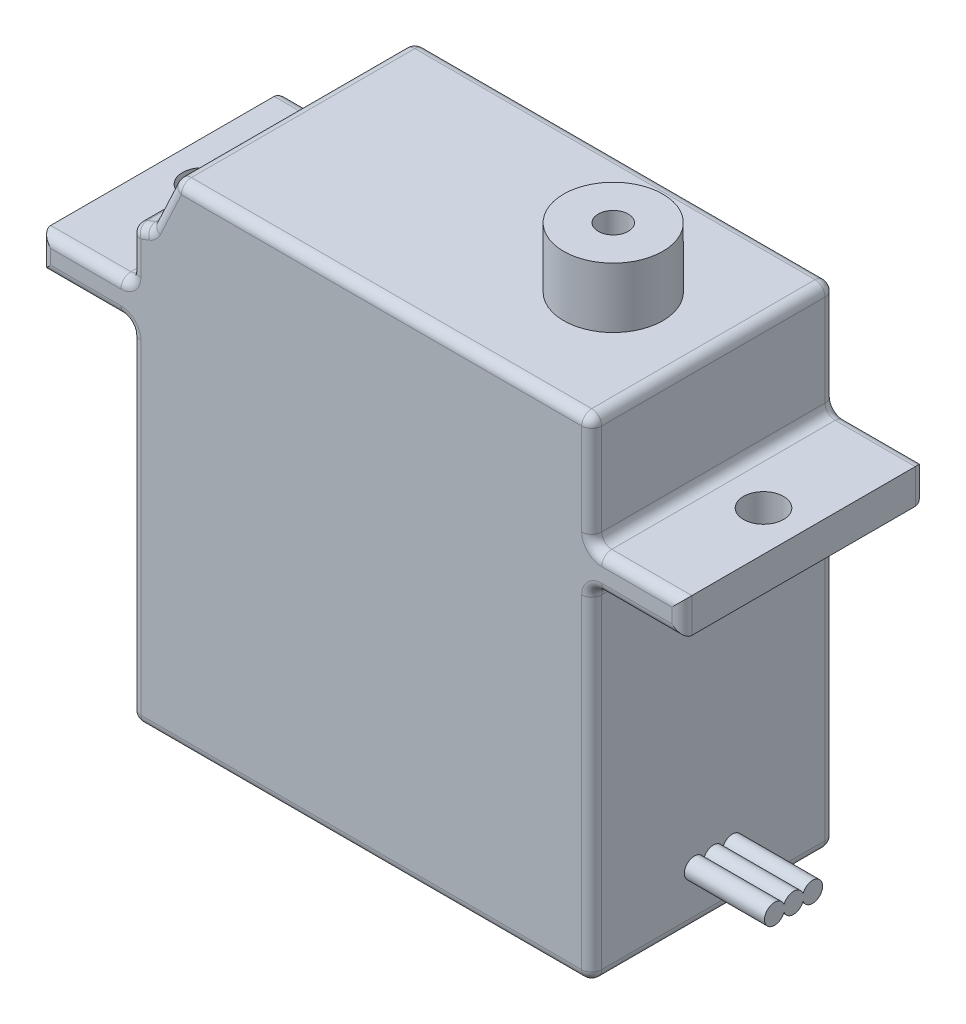
SolidWorks part; units mm, degrees
ref_plane "Plan de face" through (0, 0, 0) normal (0, 0, 1) x (1, 0, 0)
ref_plane "Plan de dessus" through (0, 0, 0) normal (0, 1, 0) x (1, 0, 0)
ref_plane "Plan de droite" through (0, 0, 0) normal (1, 0, 0) x (0, 0, -1)
sketch "Esquisse1" plane through (0, 0, 0) normal (0, 0, 1) x (1, 0, 0)
  line L0 (11.5, -17.2) -> (-11.5, -17.2)
  line L1 (-11.5, -17.2) -> (-11.5, 0)
  line L2 (-11.5, 0) -> (-16, 0)
  line L3 (-16, 0) -> (-16, 1.72)
  line L4 (-16, 1.72) -> (-11.5, 1.72)
  line L5 (-11.5, 1.72) -> (-11.5, 4.22)
  line L6 (-11.5, 4.22) -> (-10.568, 4.5824)
  line L7 (-10.568, 4.5824) -> (-9.2974, 7.3)
  line L8 (-9.2974, 7.3) -> (11.5, 7.3)
  line L9 (11.5, 7.3) -> (11.5, 1.72)
  line L10 (11.5, 1.72) -> (16, 1.72)
  line L11 (16, 1.72) -> (16, 0)
  line L12 (16, 0) -> (11.5, 0)
  line L13 (11.5, 0) -> (11.5, -17.2)
  line L14 (-11.5, 7.3) -> (11.5, 7.3) construction
  line L15 (-11.5, 7.3) -> (-11.5, 1.72) construction
  line L16 (0, 7.3) -> (0, -17.2) construction
  line L17 (-11.5, 1.72) -> (11.5, 1.72) construction
  line L18 (-11.5, 0) -> (11.5, 0) construction
  line L19 (11.5, 1.72) -> (11.5, 0) construction
  line L20 (-11.5, 4.22) -> (-3.5777, 7.3) construction
  dimension "D1" = 23
  dimension "D2" = 1.72
  dimension "D3" = 17.2
  dimension "D4" = 24.5
  dimension "D5" = 32
  dimension "D7" = 2.5
  dimension "D8" = 1
  dimension "D9" = 3
  dimension "D10" = 8.5
extrude "Boss.-Extru.1" add sketch "Esquisse1" along normal blind 12.15
sketch "Esquisse2" plane through (0, 1.72, 0) normal (0, 1, 0) x (1, 0, 0)
  line L0 (16, -6.075) -> (-16, -6.075) construction
  line L1 (16, -12.15) -> (16, 0) construction
  line L2 (-16, -12.15) -> (-16, 0) construction
  circle A0 centre (-14, -6.075) radius 1
  circle A1 centre (14, -6.075) radius 1
  dimension "D3" = 2
  dimension "D4" = 2
  dimension "D1" = 14
  dimension "D2" = 14
extrude "Enlèv. mat.-Extru.1" cut sketch "Esquisse2" against normal through all
sketch "Esquisse4" plane through (11.5, 0, 0) normal (1, 0, 0) x (0, 0, -1)
  line L0 (-6.075, -17.2) -> (-6.075, 7.3) construction
  line L1 (-12.15, -17.2) -> (0, -17.2) construction
  line L2 (-12.15, 7.3) -> (0, 7.3) construction
  line L3 (-12.15, -14.6) -> (0, -14.6) construction
  line L4 (-12.15, -17.2) -> (-12.15, 0) construction
  line L5 (0, -17.2) -> (0, 0) construction
  circle A0 centre (-6.075, -14.6) radius 0.5
  circle A1 centre (-5.125, -14.6) radius 0.5
  circle A2 centre (-7.025, -14.6) radius 0.5
  dimension "D2" = 1
  dimension "D1" = 2.6
  dimension "D3" = 0.95
  dimension "D4" = 0.95
extrude "Boss.-Extru.4" add sketch "Esquisse4" along normal blind 4 contours A0 A2 | A2 A0 A1 | A0 A1 | A0 A2 | A0 A1
sketch "Esquisse5" plane through (0, 7.3, 0) normal (0, 1, 0) x (1, 0, 0)
  line L0 (11.5, -6.075) -> (-9.2974, -6.075) construction
  line L1 (11.5, -12.15) -> (11.5, 0) construction
  line L2 (-9.2974, -12.15) -> (-9.2974, 0) construction
  circle A0 centre (6.5, -6.075) radius 2.475
  circle A1 centre (6.5, -6.075) radius 0.75
  dimension "D1" = 4.95
  dimension "D2" = 1.5
  dimension "D3" = 5
extrude "Boss.-Extru.5" add sketch "Esquisse5" along normal blind 3
fillet "Congé1" radius 0.5 38 edges at (-13.75, 1.72, 12.15) (-13.75, 1.72, 0) (-13.75, 0, 12.15) (-13.75, 0, 0) (13.75, 0, 12.15) (13.75, 0, 0) (13.75, 1.72, 12.15) (13.75, 1.72, 0) (-11.5, 1.72, 6.075) (-11.5, 0, 6.075) (11.5, 0, 6.075) (11.5, 1.72, 6.075) (11.5, 7.3, 6.075) (-11.5, 4.22, 6.075) (-10.568, 4.5824, 6.075) (1.1013, 7.3, 0) (-9.2974, 7.3, 6.075) (-9.9327, 5.9412, 0) (-11.034, 4.4012, 0) (-11.5, 2.97, 0) (1.1013, 7.3, 12.15) (-9.9327, 5.9412, 12.15) (-11.034, 4.4012, 12.15) (-11.5, 2.97, 12.15) (11.5, 4.51, 12.15) (11.5, -8.6, 12.15) (16, 0.86, 12.15) (16, 0.86, 0) (11.5, 4.51, 0) (11.5, -8.6, 0) (11.5, -17.2, 6.075) (0, -17.2, 0) (0, -17.2, 12.15) (-11.5, -17.2, 6.075) (-11.5, -8.6, 0) (-11.5, -8.6, 12.15) (-16, 0.86, 12.15) (-16, 0.86, 0)
